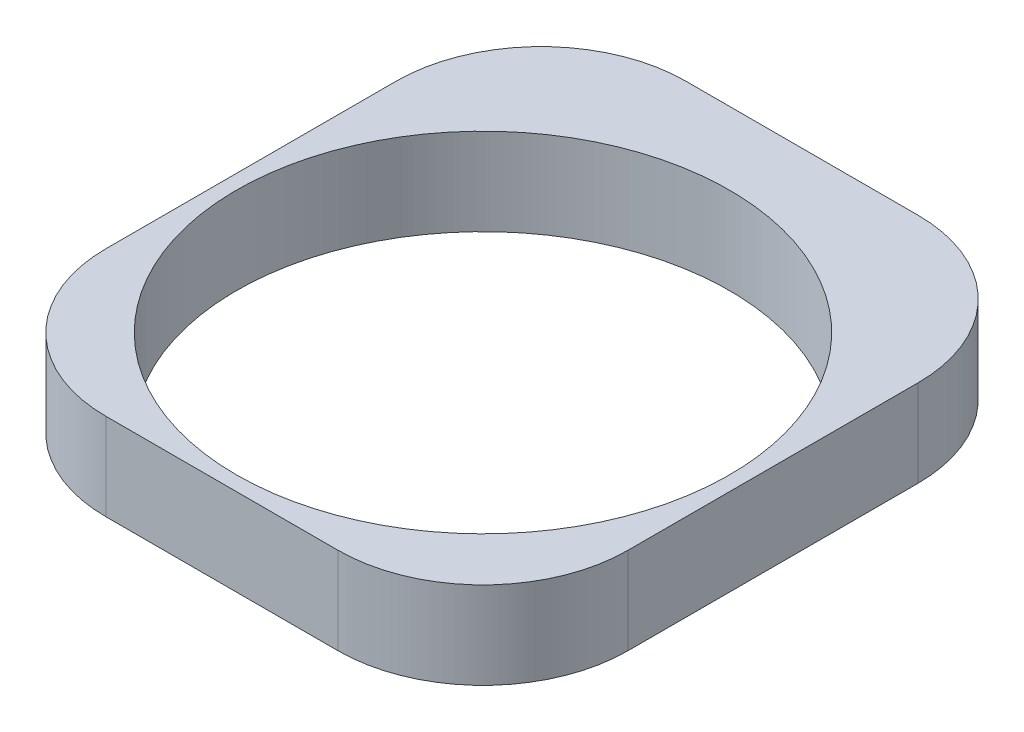
SolidWorks part; units mm, degrees
ref_plane "Front Plane" through (0, 0, 0) normal (0, 0, 1) x (1, 0, 0)
ref_plane "Top Plane" through (0, 0, 0) normal (0, 1, 0) x (1, 0, 0)
ref_plane "Right Plane" through (0, 0, 0) normal (1, 0, 0) x (0, 0, -1)
sketch "Sketch1" plane through (0, 0, 0) normal (0, 1, 0) x (1, 0, 0)
  line L1 (0, 0) -> (-180, 0)
  line L2 (0, 0) -> (0, 200)
  line L3 (0, 200) -> (-180, 200)
  line L4 (-180, 0) -> (-180, 200)
  dimension "D1" = 200
  dimension "D2" = 180
extrude "Boss-Extrude1" add sketch "Sketch1" along normal blind 30
sketch "Sketch7" plane through (0, 30, 0) normal (0, 1, 0) x (1, 0, 0)
  line L0 (0, 0) -> (0, 200) construction
  line L1 (-180, 200) -> (-180, 0) construction
  line L2 (-180, 0) -> (0, 0) construction
  circle A0 centre (-90, 90) radius 85
  dimension "D1" = 170
  dimension "D2" = 90
  dimension "D3" = 90
  dimension "D4" = 90
extrude "Cut-Extrude1" cut sketch "Sketch7" against normal blind 40
fillet "Fillet1" radius 50 1 edges at (0, 15, -200)
fillet "Fillet2" radius 50 1 edges at (0, 15, 0)
fillet "Fillet3" radius 50 1 edges at (-180, 15, 0)
fillet "Fillet4" radius 50 1 edges at (-180, 15, -200)
